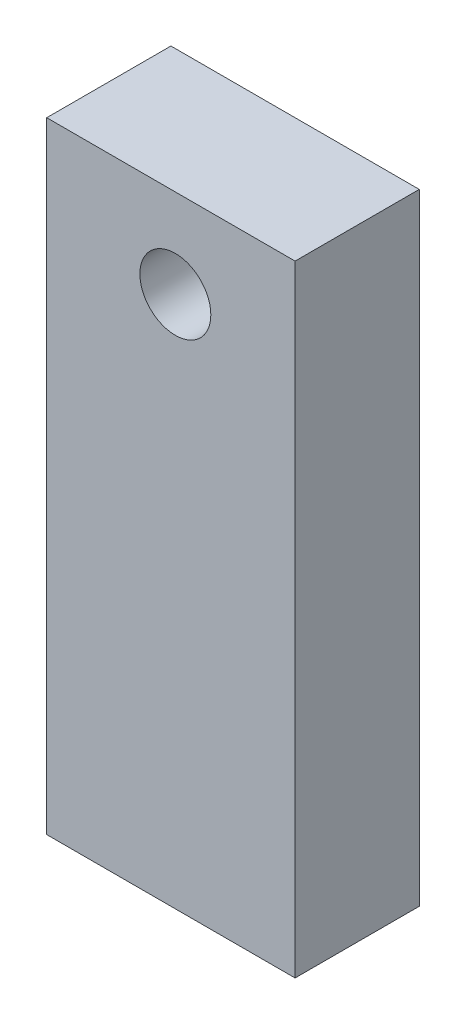
SolidWorks part; units mm, degrees
ref_plane "Спереди" through (0, 0, 0) normal (0, 0, 1) x (1, 0, 0)
ref_plane "Сверху" through (0, 0, 0) normal (0, 1, 0) x (1, 0, 0)
ref_plane "Справа" through (0, 0, 0) normal (1, 0, 0) x (0, 0, -1)
sketch "Эскиз1" plane through (0, 0, 0) normal (0, 1, 0) x (1, 0, 0)
  line L1 (0, 0) -> (28, 0)
  line L2 (0, 0) -> (0, -14)
  line L3 (0, -14) -> (28, -14)
  line L4 (28, 0) -> (28, -14)
extrude "Вытянуть1" add sketch "Эскиз1" along normal blind 70
sketch "Эскиз2" plane through (0, 0, 14) normal (0, 0, 1) x (1, 0, 0)
  line L0 (14.5, 70) -> (14.5, 42.6899) construction
  line L2 (0, 70) -> (28, 70) construction
  circle A0 centre (14.5, 60) radius 4
  dimension "D1" = 10
extrude "Вытянуть2" cut sketch "Эскиз2" against normal through all
